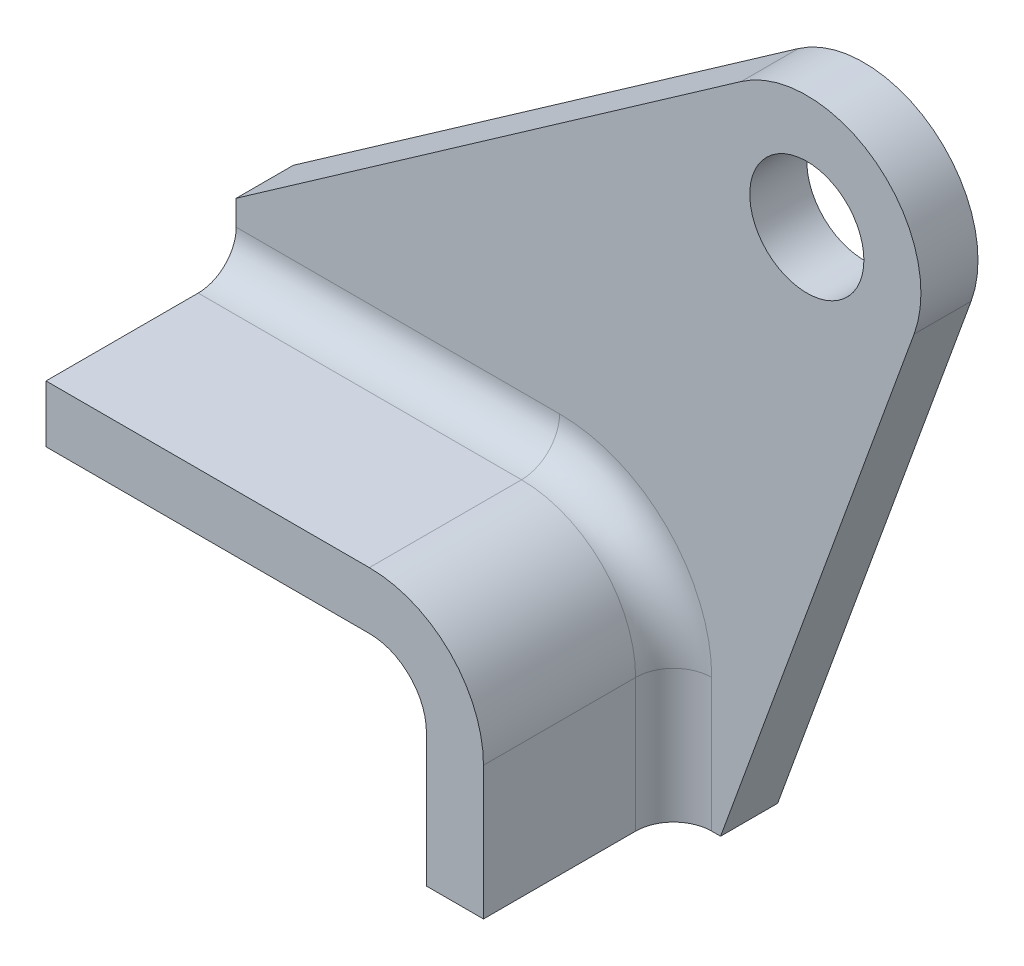
SolidWorks part; units mm, degrees
material "Простая углеродистая сталь"
ref_plane "Front" through (0, 0, 0) normal (0, 0, 1) x (1, 0, 0)
ref_plane "Top" through (0, 0, 0) normal (0, 1, 0) x (1, 0, 0)
ref_plane "Right" through (0, 0, 0) normal (1, 0, 0) x (0, 0, -1)
sketch "Эскиз1" plane through (0, 0, 0) normal (0, 0, 1) x (1, 0, 0)
  line L0 (-40, 0) -> (-6, 0)
  line L2 (10.9319, -20) -> (31.2763, 35.8958)
  line L3 (13.1171, 49.8298) -> (-40, 12.6368)
  line L4 (-40, 12.6368) -> (-40, 0)
  line L5 (0, -6) -> (0, -20)
  line L6 (0, -20) -> (10.9319, -20)
  arc A0 (31.2763, 35.8958) -> (13.1171, 49.8298) centre (20, 40) ccw
  circle A1 centre (20, 40) radius 6
  arc A2 (-6, 0) -> (0, -6) centre (-6, -6) cw
  point P9 (0, 0)
  point P10 (16.1792, -20)
  point P11 (-40, 20.9509)
  point P12 (-40, 5.3195)
  point P16 (0, 0)
  dimension "D1" = 40
  dimension "D5" = 12
  dimension "D6" = 12
  dimension "D9" = 6
  dimension "D2" = 20
  dimension "D3" = 20
  dimension "D4" = 40
  dimension "D7" = 35
  dimension "D8" = 35
extrude "Бобышка-Вытянуть1" add sketch "Эскиз1" along normal blind 6
sketch "Эскиз2" plane through (0, 0, 6) normal (0, 0, 1) x (1, 0, 0)
  line L0 (-40, 0) -> (-6, 0) construction
  line L1 (0, -6) -> (0, -20) construction
  line L2 (-40, 0) -> (-6, 0)
  line L3 (0, -6) -> (0, -20)
  line L4 (-40, 6) -> (-6, 6)
  line L5 (6, -6) -> (6, -20)
  line L6 (0, -20) -> (6, -20)
  line L7 (-40, 0) -> (-40, 6)
  arc A0 (0, -6) -> (-6, 0) centre (-6, -6) ccw construction
  arc A1 (0, -6) -> (-6, 0) centre (-6, -6) ccw
  arc A2 (6, -6) -> (-6, 6) centre (-6, -6) ccw
  dimension "D1" = 6
extrude "Бобышка-Вытянуть2" add sketch "Эскиз2" along normal blind 20
fillet "Скругление1" radius 4 3 edges at (6, -13, 6) (2.4853, 2.4853, 6) (-23, 6, 6)
